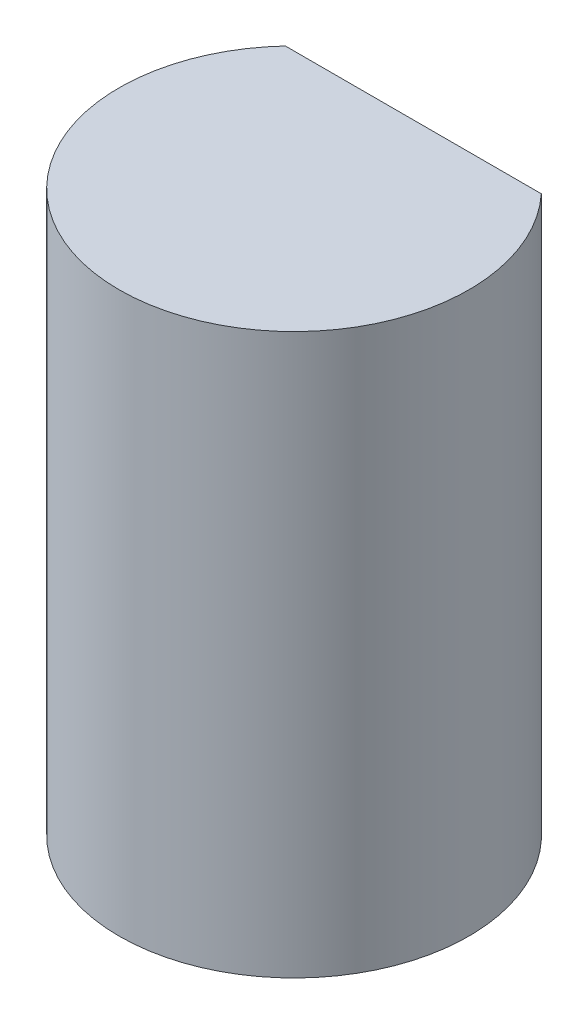
SolidWorks part; units mm, degrees
ref_plane "Front Plane" through (0, 0, 0) normal (0, 0, 1) x (1, 0, 0)
ref_plane "Top Plane" through (0, 0, 0) normal (0, 1, 0) x (1, 0, 0)
ref_plane "Right Plane" through (0, 0, 0) normal (1, 0, 0) x (0, 0, -1)
sketch "Sketch1" plane through (0, 0, 0) normal (0, 1, 0) x (1, 0, 0)
  circle A0 centre (0, 0) radius 3.9688
  dimension "D1" = 7.9375
extrude "Boss-Extrude1" add sketch "Sketch1" along normal mid plane 12.7
sketch "Sketch2" plane through (0, 6.35, 0) normal (0, 1, 0) x (1, 0, 0)
  line L0 (-2.903, 2.7063) -> (2.903, 2.7063)
  circle A0 centre (0, 0) radius 3.9688 construction
  arc A1 (2.903, 2.7063) -> (-2.903, 2.7063) centre (0, 0) ccw
extrude "Cut-Extrude1" cut sketch "Sketch2" against normal up to next
